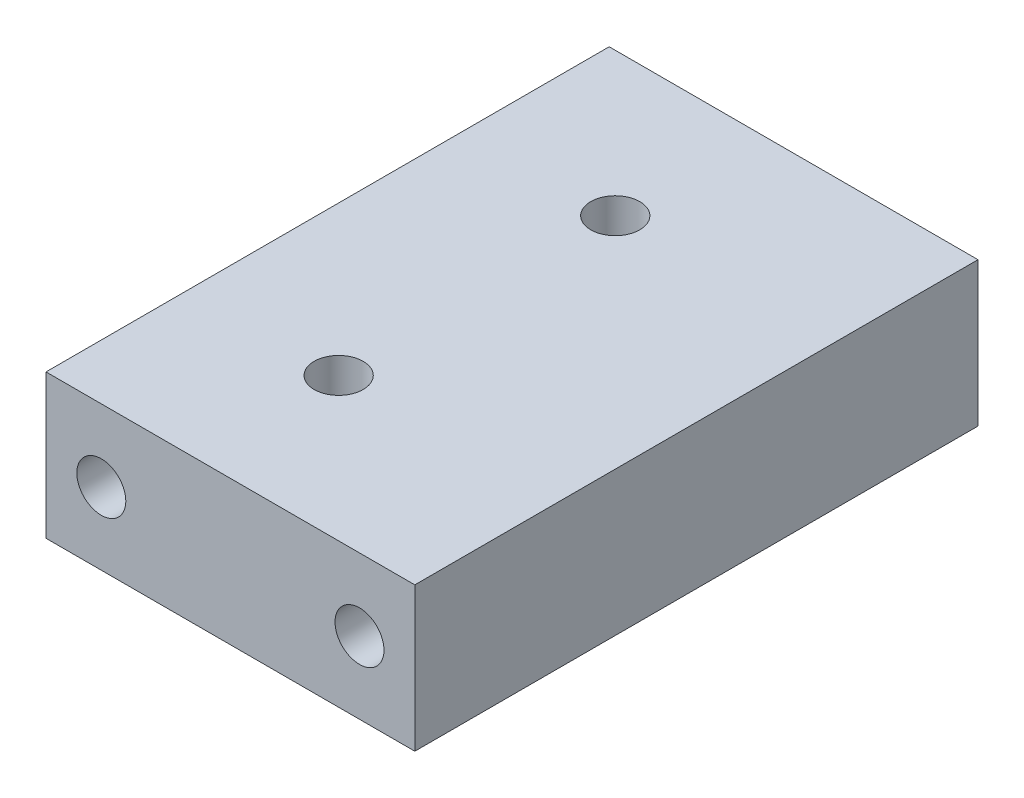
SolidWorks part; units mm, degrees
ref_plane "Front Plane" through (0, 0, 0) normal (0, 0, 1) x (1, 0, 0)
ref_plane "Top Plane" through (0, 0, 0) normal (0, 1, 0) x (1, 0, 0)
ref_plane "Right Plane" through (0, 0, 0) normal (1, 0, 0) x (0, 0, -1)
sketch "Sketch1" plane through (0, 0, 0) normal (0, 1, 0) x (1, 0, 0)
  line L1 (0, 0) -> (50.8, 0)
  line L2 (0, 0) -> (0, 77.5716)
  line L3 (0, 77.5716) -> (50.8, 77.5716)
  line L4 (50.8, 0) -> (50.8, 77.5716)
  dimension "D1" = 50.8
  dimension "D2" = 77.5716
extrude "Boss-Extrude1" add sketch "Sketch1" along normal blind 19.8501
sketch "Sketch2" plane through (0, 19.8501, 0) normal (0, 1, 0) x (1, 0, 0)
  line L0 (0, 77.5716) -> (0, 0) construction
  line L1 (50.8, 77.5716) -> (0, 77.5716) construction
  circle A0 centre (20.574, 19.7358) radius 3.3734
  circle A1 centre (20.574, 57.8358) radius 3.3734
  dimension "D1" = 6.7469
  dimension "D2" = 20.574
  dimension "D4" = 19.7358
  dimension "D3" = 38.1
extrude "Cut-Extrude1" cut sketch "Sketch2" against normal through all
sketch "Sketch3" plane through (0, 0, 0) normal (0, 0, 1) x (1, 0, 0)
  line L1 (0, 19.8501) -> (0, 0) construction
  line L2 (50.8, 19.8501) -> (50.8, 0) construction
  circle A0 centre (7.62, 9.925) radius 3.3734
  circle A1 centre (43.18, 9.925) radius 3.3734
  point P8 (0, 9.925)
  dimension "D1" = 7.62
  dimension "D2" = 7.62
  dimension "D3" = 6.7469
extrude "Cut-Extrude2" cut sketch "Sketch3" against normal through all
